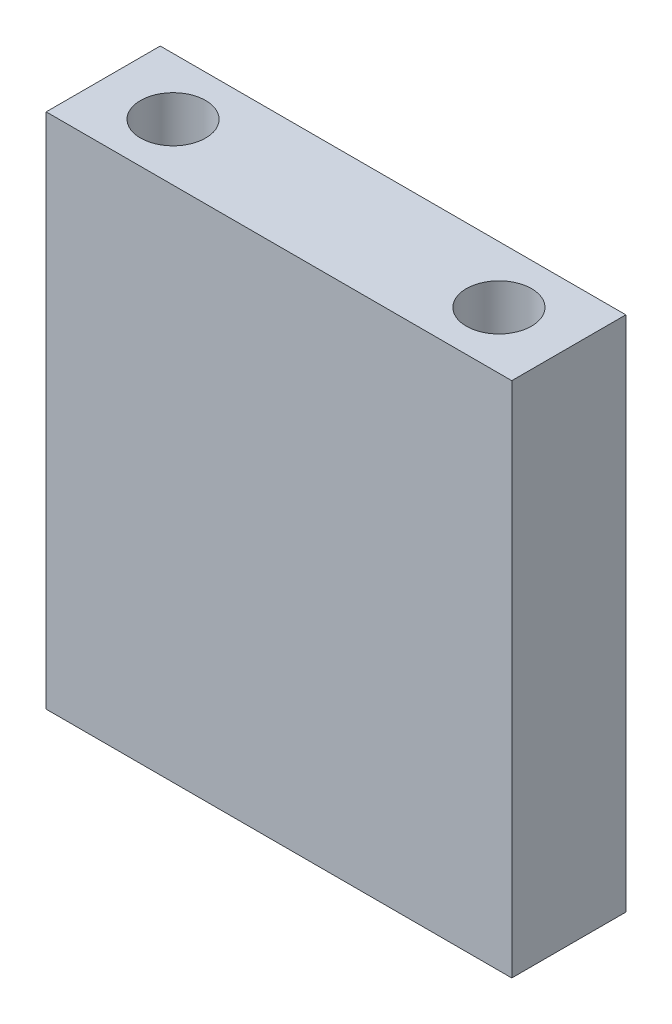
SolidWorks part; units mm, degrees
ref_plane "Front Plane" through (0, 0, 0) normal (0, 0, 1) x (1, 0, 0)
ref_plane "Top Plane" through (0, 0, 0) normal (0, 1, 0) x (1, 0, 0)
ref_plane "Right Plane" through (0, 0, 0) normal (1, 0, 0) x (0, 0, -1)
sketch "Sketch1" plane through (0, 0, 0) normal (0, 0, 1) x (1, 0, 0)
  line L1 (-14.2875, -15.875) -> (14.2875, -15.875)
  line L2 (-14.2875, -15.875) -> (-14.2875, 15.875)
  line L3 (-14.2875, 15.875) -> (14.2875, 15.875)
  line L4 (14.2875, -15.875) -> (14.2875, 15.875)
  line L5 (-14.2875, -15.875) -> (14.2875, 15.875) construction
  line L6 (-14.2875, 15.875) -> (14.2875, -15.875) construction
  point P0 (0, 0)
  dimension "D1" = 31.75
  dimension "D2" = 28.575
extrude "Boss-Extrude1" add sketch "Sketch1" along normal mid plane 7
sketch "Sketch3" plane through (0, 15.875, 0) normal (0, 1, 0) x (1, 0, 0)
  line L0 (-14.2875, 0) -> (14.2875, 0) construction
  line L1 (-14.2875, -3.5) -> (-14.2875, 3.5) construction
  line L2 (14.2875, -3.5) -> (14.2875, 3.5) construction
  line L3 (0, 3.5) -> (0, -3.5) construction
  line L4 (14.2875, 3.5) -> (-14.2875, 3.5) construction
  line L5 (14.2875, -3.5) -> (-14.2875, -3.5) construction
  circle A0 centre (-10, 0) radius 2
  circle A2 centre (10, 0) radius 2
  dimension "D2" = 4
  dimension "D1" = 10
extrude "Cut-Extrude1" cut sketch "Sketch3" against normal blind 6
